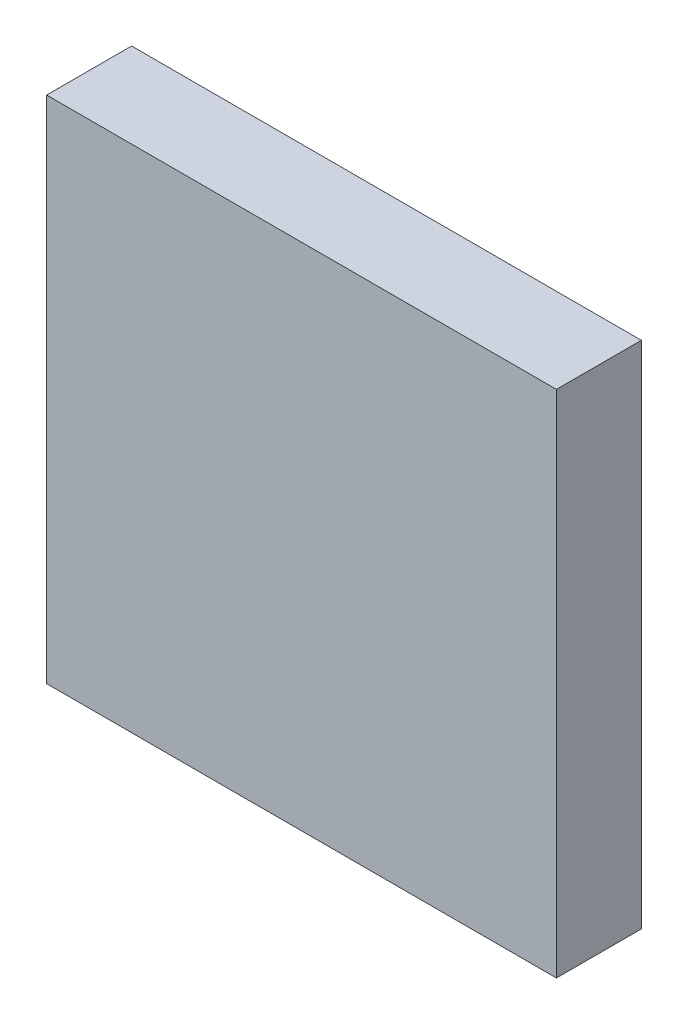
SolidWorks part; units mm, degrees
ref_plane "Front Plane" through (0, 0, 0) normal (0, 0, 1) x (1, 0, 0)
ref_plane "Top Plane" through (0, 0, 0) normal (0, 1, 0) x (1, 0, 0)
ref_plane "Right Plane" through (0, 0, 0) normal (1, 0, 0) x (0, 0, -1)
sketch "Sketch1" plane through (0, 0, 0) normal (0, 0, 1) x (1, 0, 0)
  line L1 (7.5, -7.5) -> (-7.5, -7.5)
  line L2 (7.5, -7.5) -> (7.5, 7.5)
  line L3 (7.5, 7.5) -> (-7.5, 7.5)
  line L4 (-7.5, -7.5) -> (-7.5, 7.5)
  line L5 (7.5, -7.5) -> (-7.5, 7.5) construction
  line L6 (7.5, 7.5) -> (-7.5, -7.5) construction
  point P0 (0, 0)
  dimension "D1" = 15
  dimension "D2" = 15
extrude "Boss-Extrude1" add sketch "Sketch1" along normal blind 2.5
